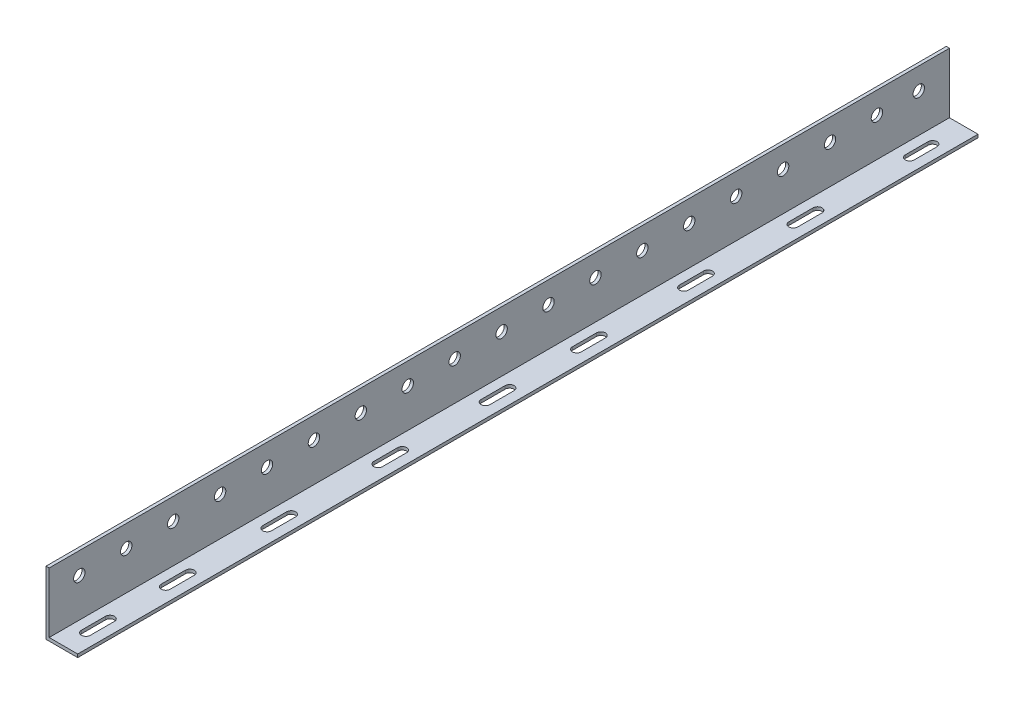
SolidWorks part; units mm, degrees
ref_plane "Front Plane" through (0, 0, 0) normal (0, 0, 1) x (1, 0, 0)
ref_plane "Top Plane" through (0, 0, 0) normal (0, 1, 0) x (1, 0, 0)
ref_plane "Right Plane" through (0, 0, 0) normal (1, 0, 0) x (0, 0, -1)
sketch "Sketch1" plane through (0, 0, 0) normal (0, 0, 1) x (1, 0, 0)
  line L0 (-9.2857, 23.8095) -> (-9.2857, -26.1905)
  line L1 (-9.2857, -26.1905) -> (15.7143, -26.1905)
  line L2 (15.7143, -26.1905) -> (15.7143, -23.6905)
  line L3 (15.7143, -23.6905) -> (-6.7857, -23.6905)
  line L4 (-6.7857, -23.6905) -> (-6.7857, 23.8095)
  line L5 (-6.7857, 23.8095) -> (-9.2857, 23.8095)
  dimension "D1" = 2.5
  dimension "D2" = 2.5
  dimension "D3" = 50
  dimension "D4" = 25
extrude "Boss-Extrude1" add sketch "Sketch1" along normal blind 710
sketch "Sketch2" plane through (-6.7857, 0, 0) normal (1, 0, 0) x (0, 0, -1)
  line L0 (-710.1981, 6.7245) -> (-0.1981, 6.665) construction
  circle A0 centre (-649.1981, 6.7194) radius 4.5
  circle A1 centre (-612.1981, 6.7163) radius 4.5
  circle A2 centre (-575.1981, 6.7132) radius 4.5
  circle A3 centre (-242.1981, 6.6853) radius 4.5
  circle A4 centre (-279.1981, 6.6884) radius 4.5
  circle A5 centre (-538.1981, 6.7101) radius 4.5
  circle A6 centre (-501.1981, 6.707) radius 4.5
  circle A7 centre (-464.1981, 6.7039) radius 4.5
  circle A8 centre (-427.1981, 6.7008) radius 4.5
  circle A9 centre (-390.1981, 6.6977) radius 4.5
  circle A10 centre (-353.1981, 6.6946) radius 4.5
  circle A11 centre (-316.1981, 6.6915) radius 4.5
  circle A12 centre (-686.1981, 6.7225) radius 4.5
  circle A13 centre (-24.1981, 6.667) radius 4.5
  circle A15 centre (-57.1981, 6.6698) radius 4.5
  circle A16 centre (-205.1981, 6.6822) radius 4.5
  circle A17 centre (-168.1981, 6.6791) radius 4.5
  circle A18 centre (-131.1981, 6.676) radius 4.5
  circle A19 centre (-94.1981, 6.6729) radius 4.5
  point P2 (0, 0)
  point P3 (0, 0)
  point P4 (0, 0)
  point P33 (0, 0)
  point P34 (0, 0)
  point P45 (0, 0)
  point P46 (0, 0)
  point P47 (-43.6937, 0.0037)
  point P48 (-63.2784, 0.0054)
  point P49 (-89.0334, 0.0076)
  point P50 (-112.9107, 0.0096)
  point P51 (-130.8857, 0.0111)
  point P52 (-155.5676, -2.3101)
  point P53 (-151.5434, 0.0129)
  point P54 (-178.0587, 0.0151)
  point P55 (-86.7332, 0.0074)
  point P56 (0, 0)
  dimension "D12" = 37
  dimension "D13" = 24
  dimension "D15" = 37
  dimension "D16" = 37
  dimension "D20" = 37
  dimension "D21" = 33
  dimension "D2" = 37
  dimension "D3" = 37
  dimension "D4" = 37
  dimension "D5" = 37
  dimension "D6" = 37
  dimension "D7" = 37
  dimension "D8" = 37
  dimension "D9" = 37
  dimension "D10" = 37
  dimension "D11" = 37
  dimension "D14" = 24
  dimension "D17" = 37
  dimension "D18" = 37
  dimension "D19" = 37
extrude "Cut-Extrude1" cut sketch "Sketch2" against normal blind 10
sketch "Sketch3" plane through (0, -23.6905, 0) normal (0, 1, 0) x (1, 0, 0)
  line L0 (4.4643, -700) -> (4.4643, 0) construction
  line L2 (15.7143, 0) -> (-6.7857, 0) construction
  line L8 (0.9643, -220.6153) -> (0.9643, -201.6153)
  line L9 (7.9643, -220.6153) -> (7.9643, -201.6153)
  line L12 (0.9631, -134.2658) -> (0.964, -115.2658)
  line L13 (7.965, -134.2683) -> (7.964, -115.2683)
  line L14 (1.1164, -42.7058) -> (1.1164, -24.7058)
  line L15 (8.1164, -42.7058) -> (8.1164, -24.7058)
  line L17 (0.9443, -305.0188) -> (0.9443, -286.0188)
  line L18 (7.9443, -305.0188) -> (7.9443, -286.0188)
  line L21 (0.9425, -377.0785) -> (0.9425, -358.0785)
  line L22 (7.9425, -377.0785) -> (7.9425, -358.0785)
  line L25 (0.9371, -461.704) -> (0.9371, -442.704)
  line L26 (7.9371, -461.704) -> (7.9371, -442.704)
  line L29 (0.9829, -549.3306) -> (0.9829, -530.3306)
  line L30 (7.9829, -549.3306) -> (7.9829, -530.3306)
  line L31 (0.9308, -629.2219) -> (0.9308, -610.2219)
  line L32 (7.9308, -629.2219) -> (7.9308, -610.2219)
  line L33 (0.9253, -692.1952) -> (0.9253, -673.1952)
  line L34 (7.9253, -692.1952) -> (7.9253, -673.1952)
  arc A6 (0.9643, -220.6153) -> (7.9643, -220.6153) centre (4.4643, -220.6963) ccw
  arc A7 (0.9643, -201.6153) -> (7.9643, -201.6153) centre (4.4643, -201.664) cw
  arc A10 (0.9631, -134.2658) -> (7.965, -134.2683) centre (4.464, -134.4098) ccw
  arc A11 (0.964, -115.2658) -> (7.964, -115.2683) centre (4.464, -115.267) cw
  arc A14 (1.1164, -24.7058) -> (8.1164, -24.7058) centre (4.6164, -24.7058) cw
  arc A15 (1.1164, -42.7058) -> (8.1164, -42.7058) centre (4.6164, -42.7058) ccw
  arc A16 (0.9443, -305.0188) -> (7.9443, -305.0188) centre (4.4443, -305.0998) ccw
  arc A17 (0.9443, -286.0188) -> (7.9443, -286.0188) centre (4.4443, -286.0676) cw
  arc A20 (0.9425, -377.0785) -> (7.9425, -377.0785) centre (4.4425, -377.1595) ccw
  arc A21 (0.9425, -358.0785) -> (7.9425, -358.0785) centre (4.4425, -358.1273) cw
  arc A24 (0.9371, -461.704) -> (7.9371, -461.704) centre (4.4371, -461.785) ccw
  arc A25 (0.9371, -442.704) -> (7.9371, -442.704) centre (4.4371, -442.7528) cw
  arc A28 (0.9829, -549.3306) -> (7.9829, -549.3306) centre (4.4829, -549.4116) ccw
  arc A29 (0.9829, -530.3306) -> (7.9829, -530.3306) centre (4.4829, -530.3793) cw
  arc A30 (0.9308, -629.2219) -> (7.9308, -629.2219) centre (4.4308, -629.3029) ccw
  arc A31 (0.9308, -610.2219) -> (7.9308, -610.2219) centre (4.4308, -610.2707) cw
  arc A32 (0.9253, -692.1952) -> (7.9253, -692.1952) centre (4.4253, -692.2762) ccw
  arc A33 (0.9253, -673.1952) -> (7.9253, -673.1952) centre (4.4253, -673.244) cw
  point P13 (4.4643, -110.7607)
  point P20 (0, 0)
  point P43 (4.4643, -134.2658)
  point P46 (4.4643, -246.9543)
  point P49 (4.4643, -228.2802)
  point P50 (4.4643, -244.2746)
  point P51 (4.4643, -238.8118)
  dimension "D1" = 7
  dimension "D2" = 18
  dimension "D7" = 7
  dimension "D3" = 18
  dimension "D4" = 7
  dimension "D5" = 19
  dimension "D6" = 19
  dimension "D8" = 19
  dimension "D9" = 19
  dimension "D10" = 7
extrude "Cut-Extrude2" cut sketch "Sketch3" against normal blind 10
